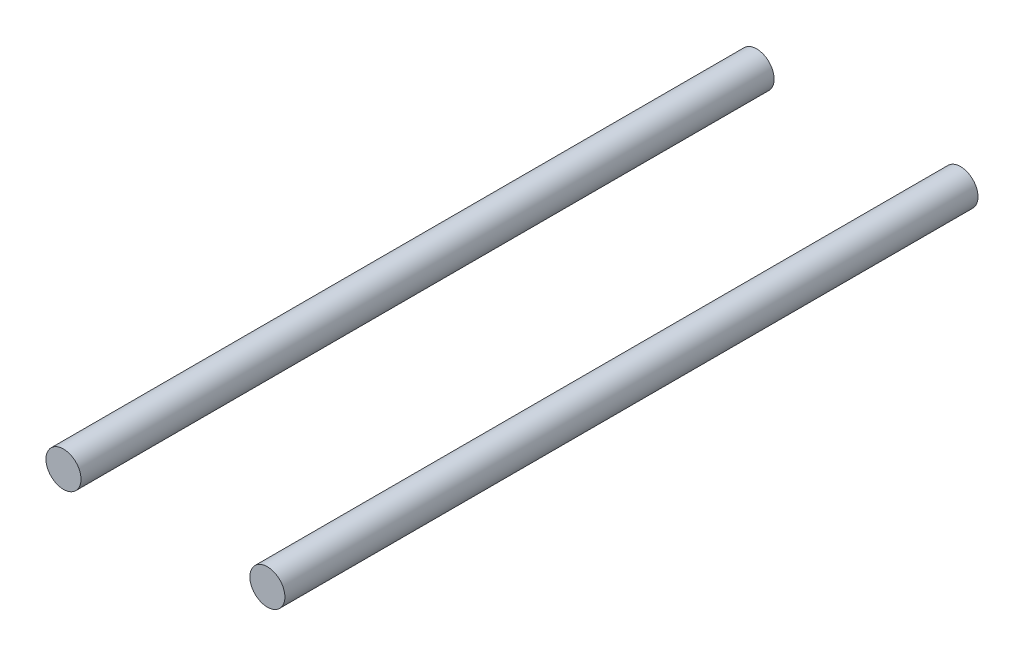
SolidWorks part; units mm, degrees
ref_plane "Front Plane" through (0, 0, 0) normal (0, 0, 1) x (1, 0, 0)
ref_plane "Top Plane" through (0, 0, 0) normal (0, 1, 0) x (1, 0, 0)
ref_plane "Right Plane" through (0, 0, 0) normal (1, 0, 0) x (0, 0, -1)
sketch "Sketch1" plane through (0, 0, 0) normal (0, 0, 1) x (1, 0, 0)
  line L0 (-29.885, 0) -> (29.885, 0) construction
  line L1 (-24.75, 0) -> (-24.75, -14.0596) construction
  line L2 (24.75, 0) -> (24.75, -13.2073) construction
  circle A0 centre (-29.885, 0) radius 5.135
  circle A1 centre (29.885, 0) radius 5.135
  point P9 (-18.9295, -14.0596)
  dimension "D1" = 10.27
  dimension "D2" = 49.5
extrude "Boss-Extrude1" add sketch "Sketch1" along normal blind 203.2
